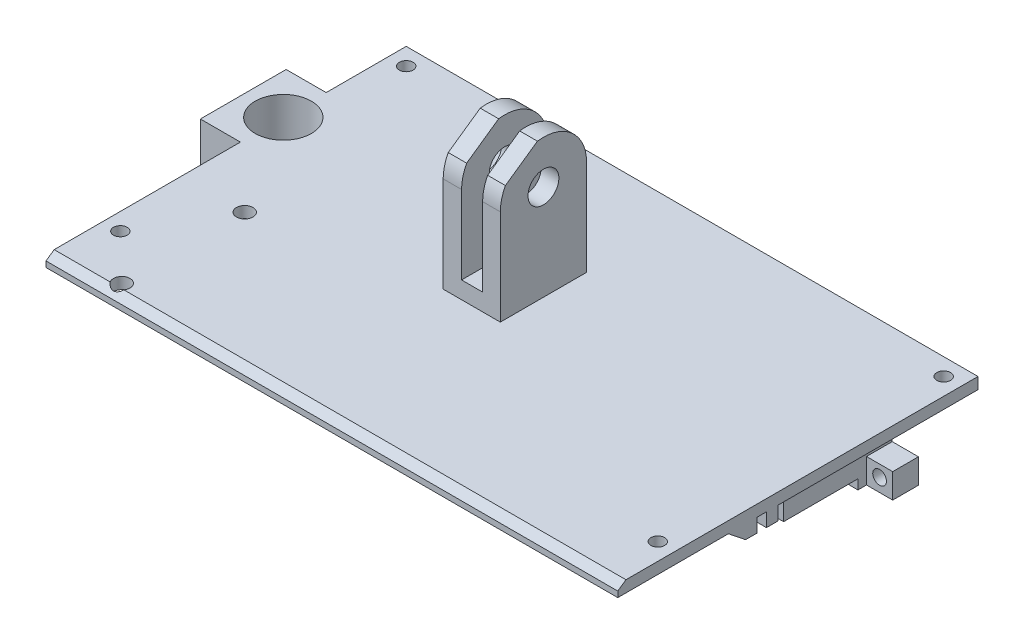
SolidWorks part; units mm, degrees
other "标注1"
sketch "草图30" plane through (-53.9, -44.7, 30) normal (-0.0815, -0.3453, 0.9349) x (0.9738, -0.2273, 0.0009)
other "标注2"
sketch "草图31" plane through (-53.9, -44.7, 30) normal (-0.0815, -0.3453, 0.9349) x (0.9738, -0.2273, 0.0009)
other "标注3"
sketch "草图32" plane through (-53.9, -44.7, 30) normal (-0.0964, -0.7087, 0.6989) x (0.9696, 0.0917, 0.2268)
ref_plane "前视基准面" through (0, 0, 0) normal (0, 0, 1) x (1, 0, 0)
ref_plane "上视基准面" through (0, 0, 0) normal (0, 1, 0) x (1, 0, 0)
ref_plane "右视基准面" through (0, 0, 0) normal (1, 0, 0) x (0, 0, -1)
other "Configuration Table"
sketch "草图1" plane through (0, 0, 0) normal (1, 0, 0) x (0, 0, -1)
  line L0 (0, -2.7) -> (0, -13.7)
  line L1 (-7.54, 0) -> (7.54, 0)
  line L2 (-7.54, 0) -> (-7.54, -13.7)
  line L3 (-7.54, -13.7) -> (7.54, -13.7)
  line L4 (7.54, 0) -> (7.54, -13.7)
  circle A0 centre (0, 0) radius 2.7
  circle A1 centre (0, 0) radius 7.54
  dimension "D1" = 5.4
  dimension "D3" = 11
  dimension "D2" = 4.84
extrude "凸台-拉伸1" add sketch "草图1" along normal blind 3.1 contours L0 A1 L1 A0 | L1 A1 L0 A0 | A1 L2 L3 L0 | L1 A1 A0 | A1 L0 L3 L4
sketch "草图2" plane through (0, -13.7, 0) normal (0, -1, 0) x (1, 0, 0)
  line L1 (3.1, 7.54) -> (-6.9, 7.54)
  line L2 (3.1, 7.54) -> (3.1, -7.54)
  line L3 (3.1, -7.54) -> (-6.9, -7.54)
  line L4 (0, 7.54) -> (0, -7.54)
  line L5 (0, -7.54) -> (3.1, -7.54)
  line L6 (3.1, -7.54) -> (3.1, 7.54)
  line L7 (3.1, 7.54) -> (0, 7.54)
  line L8 (0, 7.54) -> (0, -7.54)
  line L9 (0, -7.54) -> (3.1, -7.54)
  line L10 (3.1, -7.54) -> (3.1, 7.54)
  line L11 (3.1, 7.54) -> (0, 7.54)
  line L12 (-6.9, 7.54) -> (-6.9, -7.54)
  line L13 (-6.9, 7.54) -> (-3.68, 7.54)
  line L14 (-6.9, 7.54) -> (-6.9, -7.54)
  line L15 (-6.9, -7.54) -> (-3.68, -7.54)
  line L16 (-3.68, 7.54) -> (-3.68, -7.54)
  line M9 (0, 7.54) -> (0, -7.54)
  line M10 (0, -7.54) -> (3.1, -7.54)
  line M11 (3.1, -7.54) -> (3.1, 7.54)
  line M12 (3.1, 7.54) -> (0, 7.54)
  dimension "D2" = 10
  dimension "D3" = 3.22
  dimension "D1" = 0
extrude "凸台-拉伸2" add sketch "草图2" along normal blind 3 contours M12 M9 M10 M11 | L1 L16 L3 M9 | L16 L1 L12 L3
sketch "草图3" plane through (0, -13.7, 0) normal (0, 1, 0) x (1, 0, 0)
  line L1 (-6.9, 7.54) -> (-3.68, 7.54)
  line L2 (-6.9, 7.54) -> (-6.9, -7.54)
  line L3 (-6.9, -7.54) -> (-3.68, -7.54)
  line L4 (-6.9, -7.54) -> (0, -7.54)
  line L5 (0, -7.54) -> (0, 7.54)
  line L6 (0, 7.54) -> (-6.9, 7.54)
  line L7 (-6.9, 7.54) -> (-6.9, -7.54)
  line L8 (-6.9, -7.54) -> (0, -7.54)
  line L9 (0, -7.54) -> (0, 7.54)
  line L10 (0, 7.54) -> (-6.9, 7.54)
  line L11 (-6.9, 7.54) -> (-6.9, -7.54)
  line L12 (-3.68, 7.54) -> (-3.68, -7.54)
  line M5 (-6.9, -7.54) -> (0, -7.54)
  line M7 (0, 7.54) -> (-6.9, 7.54)
  line M8 (-6.9, 7.54) -> (-6.9, -7.54)
  dimension "D2" = 3.22
  dimension "D1" = 0
extrude "凸台-拉伸3" add sketch "草图3" along normal blind 24 contours L12 M7 M8 M5
sketch "草图4" plane through (-6.9, 0, 0) normal (-1, 0, 0) x (0, 0, 1)
  line L3 (7.54, -16.7) -> (7.54, 0)
  line L4 (-7.54, -16.7) -> (7.54, -16.7)
  line L5 (-7.54, 0) -> (-7.54, -16.7)
  line L6 (7.54, -16.7) -> (7.54, 0)
  line L7 (-7.54, -16.7) -> (7.54, -16.7)
  line L8 (-7.54, 0) -> (-7.54, -16.7)
  line L10 (7.54, -16.7) -> (7.54, 10.3)
  line L11 (7.54, 10.3) -> (-7.54, 10.3)
  line L12 (-7.54, 10.3) -> (-7.54, -16.7)
  line L13 (-7.54, -16.7) -> (7.54, -16.7)
  line L14 (7.54, -16.7) -> (7.54, 10.3)
  line L15 (7.54, 10.3) -> (-7.54, 10.3)
  line L16 (-7.54, 10.3) -> (-7.54, -16.7)
  line L17 (-7.54, -16.7) -> (7.54, -16.7)
  circle A0 centre (0, 0) radius 2.7 construction
  arc A1 (7.54, 0) -> (-7.54, 0) centre (0, 0) ccw
  arc A2 (7.54, 0) -> (-7.54, 0) centre (0, 0) ccw
  circle A3 centre (0, 0) radius 2.7
  line M9 (7.54, -16.7) -> (7.54, 10.3)
  line M10 (7.54, 10.3) -> (-7.54, 10.3)
  line M11 (-7.54, 10.3) -> (-7.54, -16.7)
  dimension "D1" = 0
  dimension "D2" = 0
extrude "切除-拉伸1" cut sketch "草图4" against normal blind 24 contours A2 M9 M10 M11 | A3
sketch "草图5" plane through (0, -16.7, 0) normal (0, -1, 0) x (1, 0, 0)
  line L0 (-6.9, 7.54) -> (3.1, -7.54)
  line L2 (-46.9, -20) -> (43.1, -20)
  line L3 (-46.9, -20) -> (-46.9, 20)
  line L4 (3.1, 7.54) -> (-6.9, 7.54)
  line L5 (-6.9, 7.54) -> (-6.9, -7.54)
  line L6 (-6.9, -7.54) -> (3.1, -7.54)
  line L7 (3.1, -7.54) -> (3.1, 7.54)
  line L8 (3.1, 7.54) -> (-6.9, 7.54)
  line L9 (-6.9, 7.54) -> (-6.9, -7.54)
  line L10 (-6.9, -7.54) -> (3.1, -7.54)
  line L11 (3.1, -7.54) -> (3.1, 7.54)
  line L12 (-46.9, 20) -> (43.1, 20)
  line L13 (43.1, -20) -> (43.1, 20)
  line L14 (-46.9, -20) -> (43.1, 20) construction
  line L15 (-46.9, 20) -> (43.1, -20) construction
  point P2 (-1.9, 0)
  line M7 (3.1, 7.54) -> (-6.9, 7.54)
  line M8 (-6.9, 7.54) -> (-6.9, -7.54)
  line M9 (-6.9, -7.54) -> (3.1, -7.54)
  line M10 (3.1, -7.54) -> (3.1, 7.54)
  dimension "D2" = 90
  dimension "D3" = 40
  dimension "D1" = 0
extrude "凸台-拉伸4" add sketch "草图5" along normal blind 2 contours L2 L13 L12 L3 M7 M10 M9 M8 | L0 M8 M9 | L0 M7 M10
sketch "草图6" plane through (0, -18.7, 0) normal (0, -1, 0) x (1, 0, 0)
  line L0 (-39.9, -20) -> (36.1, -20)
  line L1 (-41.9, -20) -> (-41.9, 3)
  line L2 (-39.9, -20) -> (36.1, -20)
  line L3 (-39.9, -20) -> (-39.9, 1)
  line L4 (-46.9, -20) -> (43.1, -20)
  line L5 (43.1, -20) -> (43.1, 20)
  line L6 (43.1, 20) -> (-46.9, 20)
  line L7 (-46.9, 20) -> (-46.9, -20)
  line L8 (-46.9, -20) -> (43.1, -20)
  line L9 (43.1, -20) -> (43.1, 20)
  line L10 (43.1, 20) -> (-46.9, 20)
  line L11 (-46.9, 20) -> (-46.9, -20)
  line L12 (-39.9, 1) -> (36.1, 1)
  line L13 (36.1, -20) -> (36.1, 1)
  line L14 (-41.9, 3) -> (38.1, 3)
  line L15 (38.1, -20) -> (38.1, 3)
  line L17 (-41.9, -20) -> (38.1, -20)
  line L18 (-41.9, -20) -> (-41.9, -22)
  line L19 (-41.9, -22) -> (38.1, -22)
  line L20 (38.1, -20) -> (38.1, -22)
  point P7 (-1.9, -20)
  line M11 (-46.9, -20) -> (43.1, -20)
  dimension "D2" = 76
  dimension "D3" = 21
  dimension "D5" = 2
  dimension "D1" = 0
  dimension "D4" = 2
extrude "凸台-拉伸6" add sketch "草图6" along normal blind 18 and the other way up to surface contours L15 L14 L1 L3 L12 L13 M11 | L20 L18 L19 M11
sketch "草图7" plane through (0, -36.7, 0) normal (0, -1, 0) x (1, 0, 0)
  line L1 (38.1, 3) -> (28.1, 3)
  line L2 (38.1, 3) -> (38.1, -7)
  line L3 (38.1, -7) -> (28.1, -7)
  line L4 (-41.9, -22) -> (38.1, -22)
  line L5 (38.1, -22) -> (38.1, 3)
  line L6 (38.1, 3) -> (-41.9, 3)
  line L7 (-41.9, 3) -> (-41.9, -22)
  line L8 (-41.9, -22) -> (38.1, -22)
  line L9 (38.1, -22) -> (38.1, 3)
  line L10 (38.1, 3) -> (-41.9, 3)
  line L11 (-41.9, 3) -> (-41.9, -22)
  line L12 (28.1, 3) -> (28.1, -7)
  line L13 (-41.9, -22) -> (-31.9, -22)
  line L14 (-41.9, -22) -> (-41.9, -12)
  line L15 (-41.9, -12) -> (-31.9, -12)
  line L16 (-31.9, -22) -> (-31.9, -12)
  line M9 (-41.9, -22) -> (38.1, -22)
  line M10 (38.1, -22) -> (38.1, 3)
  line M11 (38.1, 3) -> (-41.9, 3)
  line M13 (36.1, 1) -> (36.1, -20)
  line M14 (36.1, -20) -> (-39.9, -20)
  line M15 (-39.9, -20) -> (-39.9, 1)
  line M16 (-39.9, 1) -> (36.1, 1)
  dimension "D2" = 10
  dimension "D3" = 10
  dimension "D4" = 10
  dimension "D5" = 10
  dimension "D1" = 0
extrude "切除-拉伸2" cut sketch "草图7" against normal up to surface (18 mm away) contours L12 L3 M11 M16 M13 M10 | L16 L15 L11 M9 M14 M15 up to face at (-1.9, -18.7, -4.25)
sketch "草图8" plane through (0, -18.7, 0) normal (0, -1, 0) x (1, 0, 0)
  line L0 (-41.9, 3) -> (-41.9, 11)
  line L1 (-43.9, 9) -> (-43.9, 14.65)
  line L2 (-41.9, 11) -> (8.1, 11)
  line L3 (-41.9, 11) -> (-41.9, 12.65)
  line L4 (-41.9, 12.65) -> (8.1, 12.65)
  line L5 (8.1, 11) -> (8.1, 12.65)
  line L6 (-43.9, 14.65) -> (10.1, 14.65)
  line L7 (10.1, 9) -> (10.1, 14.65)
  line L8 (-43.9, 9) -> (10.1, 9)
  line L9 (-41.9, 12.65) -> (-43.9, 12.65)
  line L10 (-41.9, 11) -> (-43.9, 11)
  line L11 (8.1, 12.65) -> (10.1, 12.65)
  line L12 (36.1, -7) -> (38.1, -7)
  line L13 (38.1, -7) -> (38.1, -20)
  line L14 (38.1, -20) -> (43.1, -20)
  line L15 (43.1, -20) -> (43.1, 20)
  line L16 (43.1, 20) -> (-46.9, 20)
  line L17 (-46.9, 20) -> (-46.9, -20)
  line L18 (-46.9, -20) -> (-41.9, -20)
  line L19 (-41.9, -20) -> (-41.9, -22)
  line L20 (-41.9, -22) -> (-31.9, -22)
  line L21 (-31.9, -22) -> (-31.9, -20)
  line L22 (-31.9, -20) -> (36.1, -20)
  line L23 (36.1, -20) -> (36.1, -7)
  line L24 (36.1, -7) -> (38.1, -7)
  line L25 (38.1, -7) -> (38.1, -20)
  line L26 (38.1, -20) -> (43.1, -20)
  line L27 (43.1, -20) -> (43.1, 20)
  line L28 (43.1, 20) -> (-46.9, 20)
  line L29 (-46.9, 20) -> (-46.9, -20)
  line L30 (-46.9, -20) -> (-41.9, -20)
  line L31 (-41.9, -20) -> (-41.9, -22)
  line L32 (-41.9, -22) -> (-31.9, -22)
  line L33 (-31.9, -22) -> (-31.9, -20)
  line L34 (-31.9, -20) -> (36.1, -20)
  line L35 (36.1, -20) -> (36.1, -7)
  line L36 (8.1, 11) -> (10.1, 11)
  dimension "D2" = 8
  dimension "D3" = 50
  dimension "D4" = 1.65
  dimension "D1" = 0
  dimension "D5" = 2
extrude "凸台-拉伸8" add sketch "草图8" along normal blind 2.4 contours L4 L11 L7 L6 L1 L9 | L36 L2 L0 L8 L7 | L0 L10 L1 L8
sketch "草图9" plane through (0, -21.1, 0) normal (0, -1, 0) x (1, 0, 0)
  line L0 (43.1, -20) -> (43.1, 20) construction
  line L1 (10.1, 14.65) -> (43.1, 14.65)
  line L2 (10.1, 14.65) -> (10.1, 12.65)
  line L3 (10.1, 12.65) -> (43.1, 12.65)
  line L4 (-43.9, 12.65) -> (10.1, 12.65)
  line L5 (10.1, 12.65) -> (10.1, 14.65)
  line L6 (10.1, 14.65) -> (-43.9, 14.65)
  line L7 (-43.9, 14.65) -> (-43.9, 12.65)
  line L8 (-43.9, 12.65) -> (10.1, 12.65)
  line L9 (10.1, 12.65) -> (10.1, 14.65)
  line L10 (10.1, 14.65) -> (-43.9, 14.65)
  line L11 (-43.9, 14.65) -> (-43.9, 12.65)
  line L12 (10.1, 11) -> (-43.9, 11)
  line L13 (-43.9, 11) -> (-43.9, 9)
  line L14 (-43.9, 9) -> (10.1, 9)
  line L15 (10.1, 9) -> (10.1, 11)
  line L16 (10.1, 11) -> (-43.9, 11)
  line L17 (-43.9, 11) -> (-43.9, 9)
  line L18 (-43.9, 9) -> (10.1, 9)
  line L19 (10.1, 9) -> (10.1, 11)
  line L20 (43.1, 14.65) -> (43.1, 12.65)
  line L21 (-46.9, -20) -> (-46.9, 20) construction
  line L22 (10.1, 11) -> (43.1, 11)
  line L23 (10.1, 11) -> (10.1, 9)
  line L24 (10.1, 9) -> (43.1, 9)
  line L25 (43.1, 11) -> (43.1, 9)
  line L26 (-43.9, 11) -> (-46.9, 11)
  line L27 (-43.9, 11) -> (-43.9, 9)
  line L28 (-43.9, 9) -> (-46.9, 9)
  line L29 (-46.9, 11) -> (-46.9, 9)
  line L31 (-43.9, 14.65) -> (-46.9, 14.65)
  line L32 (-43.9, 14.65) -> (-43.9, 12.65)
  line L33 (-43.9, 12.65) -> (-46.9, 12.65)
  line L34 (-46.9, 14.65) -> (-46.9, 12.65)
  line M10 (10.1, 12.65) -> (10.1, 14.65)
  line M12 (-43.9, 14.65) -> (-43.9, 12.65)
  dimension "D1" = 0
  dimension "D2" = 0
extrude "凸台-拉伸9" add sketch "草图9" against normal up to surface (2.4 mm away) contours L20 L1 L3 M10 | L25 L22 L19 L24 | L31 L34 L33 M12 | L26 L29 L28 L17 up to face at (-16.9, -18.7, 10)
sketch "草图10" plane through (0, -21.1, 0) normal (0, -1, 0) x (1, 0, 0)
  line L1 (-46.9, 14.65) -> (-36.9, 14.65)
  line L2 (-46.9, 14.65) -> (-46.9, 12.65)
  line L3 (-46.9, 12.65) -> (-36.9, 12.65)
  line L4 (-46.9, 12.65) -> (43.1, 12.65)
  line L5 (43.1, 12.65) -> (43.1, 14.65)
  line L6 (43.1, 14.65) -> (-46.9, 14.65)
  line L7 (-46.9, 14.65) -> (-46.9, 12.65)
  line L8 (-46.9, 12.65) -> (43.1, 12.65)
  line L9 (43.1, 12.65) -> (43.1, 14.65)
  line L10 (43.1, 14.65) -> (-46.9, 14.65)
  line L11 (-46.9, 14.65) -> (-46.9, 12.65)
  line L12 (43.1, 11) -> (-46.9, 11)
  line L13 (-46.9, 11) -> (-46.9, 9)
  line L14 (-46.9, 9) -> (43.1, 9)
  line L15 (43.1, 9) -> (43.1, 11)
  line L16 (43.1, 11) -> (-46.9, 11)
  line L17 (-46.9, 11) -> (-46.9, 9)
  line L18 (-46.9, 9) -> (43.1, 9)
  line L19 (43.1, 9) -> (43.1, 11)
  line L20 (-36.9, 14.65) -> (-36.9, 12.65)
  line L21 (-36.9, 14.65) -> (-26.9, 14.65)
  line L22 (-36.9, 14.65) -> (-36.9, 12.65)
  line L23 (-36.9, 12.65) -> (-26.9, 12.65)
  line L24 (-26.9, 14.65) -> (-26.9, 12.65)
  line L25 (-36.9, 11) -> (-26.9, 11)
  line L26 (-36.9, 11) -> (-36.9, 9)
  line L27 (-36.9, 9) -> (-26.9, 9)
  line L28 (-26.9, 11) -> (-26.9, 9)
  line L29 (-36.9, 12.65) -> (-34.9, 12.65)
  line L30 (-36.9, 12.65) -> (-36.9, 11)
  line L31 (-36.9, 11) -> (-34.9, 11)
  line L32 (-34.9, 12.65) -> (-34.9, 11)
  line M9 (-46.9, 12.65) -> (43.1, 12.65)
  line M11 (43.1, 14.65) -> (-46.9, 14.65)
  line M12 (-46.9, 14.65) -> (-46.9, 12.65)
  dimension "D3" = 10
  dimension "D4" = 10
  dimension "D5" = 10
  dimension "D6" = 2
  dimension "D1" = 0
  dimension "D2" = 0
extrude "凸台-拉伸10" add sketch "草图10" along normal up to surface (15.6 mm away) contours L24 L10 L20 L23 M9 | L32 L30 L25 M9 | L28 L16 L25 L26 L18 | L20 M11 M12 M9 | L26 L16 L17 L18 up to face at (-17.9, -36.7, -2.6667)
sketch "草图11" plane through (0, -36.7, 0) normal (0, -1, 0) x (1, 0, 0)
  line L1 (-41.9, -12) -> (-53.9, -12)
  line L2 (-41.9, -12) -> (-41.9, 3)
  line L3 (-41.9, 3) -> (-53.9, 3)
  line L4 (-53.9, -12) -> (-53.9, 3)
  line L6 (28.1, 1) -> (28.1, 3)
  line L7 (28.1, 3) -> (-41.9, 3)
  line L8 (-41.9, 3) -> (-41.9, -12)
  line L9 (-41.9, -12) -> (-39.9, -12)
  line L10 (-39.9, -12) -> (-39.9, 1)
  line L11 (-39.9, 1) -> (28.1, 1)
  line L12 (28.1, 1) -> (28.1, 3)
  line L13 (28.1, 3) -> (-41.9, 3)
  line L14 (-41.9, 3) -> (-41.9, -12)
  line L15 (-41.9, -12) -> (-39.9, -12)
  line L16 (-39.9, -12) -> (-39.9, 1)
  line L17 (-39.9, 1) -> (28.1, 1)
  line M10 (-41.9, 3) -> (-41.9, -12)
  dimension "D2" = 12
  dimension "D1" = 0
extrude "凸台-拉伸11" add sketch "草图11" against normal up to surface (20 mm away) contours L4 L1 L3 M10 up to face at (-1.9, -16.7, 0)
sketch "草图12" plane through (0, -36.7, 0) normal (0, -1, 0) x (1, 0, 0)
  line L0 (-39.9, -12) -> (-53.9, 3)
  line L6 (28.1, 1) -> (28.1, 3)
  line L7 (28.1, 3) -> (-53.9, 3)
  line L8 (-53.9, 3) -> (-53.9, -12)
  line L9 (-53.9, -12) -> (-39.9, -12)
  line L10 (-39.9, -12) -> (-39.9, 1)
  line L11 (-39.9, 1) -> (28.1, 1)
  line L12 (28.1, 1) -> (28.1, 3)
  line L13 (28.1, 3) -> (-53.9, 3)
  line L14 (-53.9, 3) -> (-53.9, -12)
  line L15 (-53.9, -12) -> (-39.9, -12)
  line L16 (-39.9, -12) -> (-39.9, 1)
  line L17 (-39.9, 1) -> (28.1, 1)
  circle A0 centre (-46.9, -4.5) radius 4.115
  dimension "D2" = 8.23
  dimension "D1" = 0
extrude "切除-拉伸3" cut sketch "草图12" against normal up to surface (20 mm away) contours L0 A0 | L0 A0 up to face at (-18.0667, -16.7, -8.5)
sketch "草图13" plane through (0, -18.7, 0) normal (0, -1, 0) x (1, 0, 0)
  line L1 (-46.9, -20) -> (43.1, -20)
  line L2 (-46.9, -20) -> (-46.9, -26)
  line L3 (-46.9, -26) -> (43.1, -26)
  line L4 (43.1, -20) -> (43.1, -26)
  line L6 (38.1, -22) -> (38.1, -7)
  line L7 (38.1, -7) -> (36.1, -7)
  line L8 (36.1, -7) -> (36.1, -20)
  line L9 (36.1, -20) -> (-31.9, -20)
  line L10 (-31.9, -20) -> (-31.9, -22)
  line L11 (-31.9, -22) -> (38.1, -22)
  line L12 (38.1, -22) -> (38.1, -7)
  line L13 (38.1, -7) -> (36.1, -7)
  line L14 (36.1, -7) -> (36.1, -20)
  line L15 (36.1, -20) -> (-31.9, -20)
  line L16 (-31.9, -20) -> (-31.9, -22)
  line L17 (-31.9, -22) -> (38.1, -22)
  line L18 (-39.9, -12) -> (-46.9, -12)
  line L19 (-46.9, -12) -> (-46.9, -20)
  line L20 (-46.9, -20) -> (-41.9, -20)
  line L21 (-41.9, -20) -> (-41.9, -22)
  line L22 (-41.9, -22) -> (-31.9, -22)
  line L23 (-31.9, -22) -> (-31.9, -20)
  line L24 (-31.9, -20) -> (36.1, -20)
  line L25 (36.1, -20) -> (36.1, -7)
  line L26 (36.1, -7) -> (38.1, -7)
  line L27 (38.1, -7) -> (38.1, -20)
  line L28 (38.1, -20) -> (43.1, -20)
  line L29 (43.1, -20) -> (43.1, 9)
  line L30 (43.1, 9) -> (-46.9, 9)
  line L31 (-46.9, 9) -> (-46.9, 3)
  line L32 (-46.9, 3) -> (28.1, 3)
  line L33 (28.1, 3) -> (28.1, 1)
  line L34 (28.1, 1) -> (-39.9, 1)
  line L35 (-39.9, 1) -> (-39.9, -12)
  line L36 (-39.9, -12) -> (-46.9, -12)
  line L37 (-46.9, -12) -> (-46.9, -20)
  line L38 (-46.9, -20) -> (-41.9, -20)
  line L39 (-41.9, -20) -> (-41.9, -22)
  line L40 (-41.9, -22) -> (-31.9, -22)
  line L41 (-31.9, -22) -> (-31.9, -20)
  line L42 (-31.9, -20) -> (36.1, -20)
  line L43 (36.1, -20) -> (36.1, -7)
  line L44 (36.1, -7) -> (38.1, -7)
  line L45 (38.1, -7) -> (38.1, -20)
  line L46 (38.1, -20) -> (43.1, -20)
  line L47 (43.1, -20) -> (43.1, 9)
  line L48 (43.1, 9) -> (-46.9, 9)
  line L49 (-46.9, 9) -> (-46.9, 3)
  line L50 (-46.9, 3) -> (28.1, 3)
  line L51 (28.1, 3) -> (28.1, 1)
  line L52 (28.1, 1) -> (-39.9, 1)
  line L53 (-39.9, 1) -> (-39.9, -12)
  line M28 (-46.9, -20) -> (-41.9, -20)
  line M29 (-41.9, -20) -> (-41.9, -22)
  line M30 (-41.9, -22) -> (-31.9, -22)
  line M36 (38.1, -20) -> (43.1, -20)
  dimension "D3" = 6
  dimension "D1" = 0
  dimension "D2" = 0
extrude "凸台-拉伸12" add sketch "草图13" against normal up to surface (2 mm away) contours L17 L2 L3 L4 L12 M30 M29 M28 M36 up to face at (-46.9, -16.7, -8.615)
sketch "草图14" plane through (0, 0, 14.65) normal (0, 0, 1) x (1, 0, 0)
  line L1 (-36.9, -36.7) -> (-46.9, -36.7)
  line L2 (-36.9, -36.7) -> (-36.9, -18.7)
  line L3 (-36.9, -18.7) -> (-46.9, -18.7)
  line L4 (-46.9, -36.7) -> (-46.9, -18.7)
  line L6 (43.1, -18.7) -> (-46.9, -18.7)
  line L7 (-46.9, -18.7) -> (-46.9, -36.7)
  line L8 (-46.9, -36.7) -> (-26.9, -36.7)
  line L9 (-26.9, -36.7) -> (-26.9, -21.1)
  line L10 (-26.9, -21.1) -> (43.1, -21.1)
  line L11 (43.1, -21.1) -> (43.1, -18.7)
  line L12 (43.1, -18.7) -> (-46.9, -18.7)
  line L13 (-46.9, -18.7) -> (-46.9, -36.7)
  line L14 (-46.9, -36.7) -> (-26.9, -36.7)
  line L15 (-26.9, -36.7) -> (-26.9, -21.1)
  line L16 (-26.9, -21.1) -> (43.1, -21.1)
  line L17 (43.1, -21.1) -> (43.1, -18.7)
  line L22 (43.1, -18.7) -> (-46.9, -18.7)
  line L23 (-46.9, -18.7) -> (-46.9, -36.7)
  line L24 (-46.9, -36.7) -> (-36.9, -36.7)
  line L25 (-36.9, -36.7) -> (-36.9, -21.1)
  line L26 (-36.9, -21.1) -> (-34.9, -21.1)
  line L27 (-34.9, -21.1) -> (-34.9, -36.7)
  line L28 (-34.9, -36.7) -> (-26.9, -36.7)
  line L29 (-26.9, -36.7) -> (-26.9, -21.1)
  line L30 (-26.9, -21.1) -> (43.1, -21.1)
  line L31 (43.1, -21.1) -> (43.1, -18.7)
  line L32 (43.1, -18.7) -> (-46.9, -18.7)
  line L33 (-46.9, -18.7) -> (-46.9, -36.7)
  line L34 (-46.9, -36.7) -> (-36.9, -36.7)
  line L35 (-36.9, -36.7) -> (-36.9, -21.1)
  line L36 (-36.9, -21.1) -> (-34.9, -21.1)
  line L37 (-34.9, -21.1) -> (-34.9, -36.7)
  line L38 (-34.9, -36.7) -> (-26.9, -36.7)
  line L39 (-26.9, -36.7) -> (-26.9, -21.1)
  line L40 (-26.9, -21.1) -> (43.1, -21.1)
  line L41 (43.1, -21.1) -> (43.1, -18.7)
  line M17 (43.1, -18.7) -> (-46.9, -18.7)
  line M18 (-46.9, -18.7) -> (-46.9, -36.7)
  line M19 (-46.9, -36.7) -> (-26.9, -36.7)
  dimension "D1" = 0
  dimension "D2" = 0
extrude "切除-拉伸4" cut sketch "草图14" against normal up to surface (3.65 mm away) contours L2 M19 M17 M18 up to face at (-20.5, -26.86, 11)
sketch "草图15" plane through (0, 0, 14.65) normal (0, 0, 1) x (1, 0, 0)
  line L0 (-26.9, -21.1) -> (-36.9, -21.1)
  line L6 (-36.9, -18.7) -> (-36.9, -36.7)
  line L7 (-36.9, -36.7) -> (-26.9, -36.7)
  line L8 (-26.9, -36.7) -> (-26.9, -21.1)
  line L9 (-26.9, -21.1) -> (43.1, -21.1)
  line L10 (43.1, -21.1) -> (43.1, -18.7)
  line L11 (43.1, -18.7) -> (-36.9, -18.7)
  line L12 (-36.9, -18.7) -> (-36.9, -36.7)
  line L13 (-36.9, -36.7) -> (-26.9, -36.7)
  line L14 (-26.9, -36.7) -> (-26.9, -21.1)
  line L15 (-26.9, -21.1) -> (43.1, -21.1)
  line L16 (43.1, -21.1) -> (43.1, -18.7)
  line L17 (43.1, -18.7) -> (-36.9, -18.7)
  line M7 (-36.9, -18.7) -> (-36.9, -36.7)
  line M8 (-36.9, -36.7) -> (-26.9, -36.7)
  line M9 (-26.9, -36.7) -> (-26.9, -21.1)
  dimension "D1" = 0
extrude "切除-拉伸5" cut sketch "草图15" against normal up to surface (3.65 mm away) contours L0 M9 M7 M8 up to face at (-20.5, -26.86, 11)
sketch "草图17" plane through (0, 0, 11) normal (0, 0, 1) x (1, 0, 0)
  line L1 (-46.9, -18.7) -> (-26.9, -18.7)
  line L2 (-46.9, -18.7) -> (-46.9, -44.7)
  line L3 (-46.9, -44.7) -> (-26.9, -44.7)
  line L4 (-26.9, -18.7) -> (-26.9, -44.7)
  line L6 (-26.9, -36.7) -> (-26.9, -21.1)
  line L7 (-26.9, -21.1) -> (43.1, -21.1)
  line L8 (43.1, -21.1) -> (43.1, -18.7)
  line L9 (43.1, -18.7) -> (-46.9, -18.7)
  line L10 (-46.9, -18.7) -> (-46.9, -36.7)
  line L11 (-46.9, -36.7) -> (-26.9, -36.7)
  line L12 (-26.9, -36.7) -> (-26.9, -21.1)
  line L13 (-26.9, -21.1) -> (43.1, -21.1)
  line L14 (43.1, -21.1) -> (43.1, -18.7)
  line L15 (43.1, -18.7) -> (-46.9, -18.7)
  line L16 (-46.9, -18.7) -> (-46.9, -36.7)
  line L17 (-46.9, -36.7) -> (-26.9, -36.7)
  line M13 (-46.9, -36.7) -> (-26.9, -36.7)
  dimension "D2" = 26
  dimension "D1" = 0
extrude "凸台-拉伸13" add sketch "草图17" against normal up to surface (2 mm away) contours L4 L2 L3 M13 up to face at (-10.2333, -25.5, 9)
sketch "草图18" plane through (0, 0, 11) normal (0, 0, 1) x (1, 0, 0)
  line L0 (-35.9, -44.7) -> (-35.9, -43.9)
  line L1 (-46.9, -18.7) -> (-35.9, -18.7)
  line L2 (-46.9, -18.7) -> (-46.9, -44.7)
  line L3 (-46.9, -44.7) -> (-35.9, -44.7)
  line L4 (-35.9, -18.7) -> (-35.9, -44.7)
  line L5 (-35.9, -18.7) -> (-35.9, -19.5)
  line L6 (-26.9, -44.7) -> (-26.9, -21.1)
  line L7 (-26.9, -21.1) -> (43.1, -21.1)
  line L8 (43.1, -21.1) -> (43.1, -18.7)
  line L9 (43.1, -18.7) -> (-46.9, -18.7)
  line L10 (-46.9, -18.7) -> (-46.9, -44.7)
  line L11 (-46.9, -44.7) -> (-26.9, -44.7)
  line L12 (-26.9, -44.7) -> (-26.9, -21.1)
  line L13 (-26.9, -21.1) -> (43.1, -21.1)
  line L14 (43.1, -21.1) -> (43.1, -18.7)
  line L15 (43.1, -18.7) -> (-46.9, -18.7)
  line L16 (-46.9, -18.7) -> (-46.9, -44.7)
  line L17 (-46.9, -44.7) -> (-26.9, -44.7)
  circle A0 centre (-35.9, -42.45) radius 1.45
  circle A1 centre (-35.9, -20.95) radius 1.45
  dimension "D4" = 2.9
  dimension "D6" = 2.9
  dimension "D2" = 11
  dimension "D3" = 0.8
  dimension "D5" = 0.8
  dimension "D1" = 0
extrude "切除-拉伸6" cut sketch "草图18" against normal up to surface (2 mm away) contours L4 A1 | L4 A1 | L4 A0 | L4 A0 up to face at (-10.2333, -28.1667, 9)
sketch "草图19" plane through (0, 0, 14.65) normal (0, 0, 1) x (1, 0, 0)
  line L0 (-26.9, -44.7) -> (-26.9, -21.1) construction
  line L1 (-26.9, -44.7) -> (-26.9, -21.1)
  line L3 (-36.9, -21.1) -> (-26.9, -21.1)
  line L4 (-36.9, -18.7) -> (-36.9, -21.1)
  line L5 (-36.9, -21.1) -> (43.1, -21.1)
  line L6 (43.1, -21.1) -> (43.1, -18.7)
  line L7 (43.1, -18.7) -> (-36.9, -18.7)
  line L8 (-36.9, -18.7) -> (-36.9, -21.1)
  line L9 (-36.9, -21.1) -> (43.1, -21.1)
  line L10 (43.1, -21.1) -> (43.1, -18.7)
  line L11 (43.1, -18.7) -> (-36.9, -18.7)
  line L12 (-36.9, -21.1) -> (-36.9, -18.7)
  line L13 (-36.9, -18.7) -> (-26.9, -18.7)
  line L14 (-26.9, -21.1) -> (-26.9, -18.7)
  line M5 (-36.9, -18.7) -> (-36.9, -21.1)
  line M6 (-36.9, -21.1) -> (43.1, -21.1)
  dimension "D1" = 0
extrude "切除-拉伸7" cut sketch "草图19" against normal up to surface (3.65 mm away) contours L14 L11 M6 M5 up to face at (-34.45, -20.95, 11)
sketch "草图20" plane through (0, -36.7, 0) normal (0, -1, 0) x (1, 0, 0)
  circle A0 centre (-46.9, -4.5) radius 4.71
  dimension "D1" = 9.42
extrude "切除-拉伸8" cut sketch "草图20" against normal up to surface (20 mm away) contours A0 up to face at (-26.15, -16.7, -3.75)
sketch "草图21" plane through (0, 0, 20) normal (0, 0, 1) x (1, 0, 0)
  line L4 (43.1, -16.7) -> (-46.9, -16.7)
  line L5 (-46.9, -16.7) -> (-46.9, -18.7)
  line L6 (-46.9, -18.7) -> (43.1, -18.7)
  line L7 (43.1, -18.7) -> (43.1, -16.7)
  line L8 (43.1, -16.7) -> (-46.9, -16.7)
  line L9 (-46.9, -16.7) -> (-46.9, -18.7)
  line L10 (-46.9, -18.7) -> (43.1, -18.7)
  line L11 (43.1, -18.7) -> (43.1, -16.7)
  dimension "D1" = 0
extrude "凸台-拉伸14" add sketch "草图21" along normal blind 10
sketch "草图22" plane through (43.1, 0, 0) normal (1, 0, 0) x (0, 0, -1)
  line L12 (26, -16.7) -> (-30, -16.7)
  line L13 (-30, -16.7) -> (-30, -18.7)
  line L14 (-30, -18.7) -> (-14.65, -18.7)
  line L15 (-14.65, -18.7) -> (-14.65, -21.1)
  line L16 (-14.65, -21.1) -> (-12.65, -21.1)
  line L17 (-12.65, -21.1) -> (-12.65, -18.7)
  line L18 (-12.65, -18.7) -> (-11, -18.7)
  line L19 (-11, -18.7) -> (-11, -21.1)
  line L20 (-11, -21.1) -> (-9, -21.1)
  line L21 (-9, -21.1) -> (-9, -18.7)
  line L22 (-9, -18.7) -> (26, -18.7)
  line L23 (26, -18.7) -> (26, -16.7)
  line L24 (26, -16.7) -> (-30, -16.7)
  line L25 (-30, -16.7) -> (-30, -18.7)
  line L26 (-30, -18.7) -> (-14.65, -18.7)
  line L27 (-14.65, -18.7) -> (-14.65, -21.1)
  line L28 (-14.65, -21.1) -> (-12.65, -21.1)
  line L29 (-12.65, -21.1) -> (-12.65, -18.7)
  line L30 (-12.65, -18.7) -> (-11, -18.7)
  line L31 (-11, -18.7) -> (-11, -21.1)
  line L32 (-11, -21.1) -> (-9, -21.1)
  line L33 (-9, -21.1) -> (-9, -18.7)
  line L34 (-9, -18.7) -> (26, -18.7)
  line L35 (26, -18.7) -> (26, -16.7)
  dimension "D1" = 0
extrude "凸台-拉伸15" add sketch "草图22" along normal blind 10
sketch "草图23" plane through (0, -18.7, 0) normal (0, -1, 0) x (1, 0, 0)
  line L0 (-46.9, 30) -> (-40.9, 24)
  line L1 (-46.9, 30) -> (-40.9, 30)
  line L2 (-46.9, 30) -> (-46.9, 24)
  line L3 (-46.9, 24) -> (-40.9, 24)
  line L4 (-40.9, 30) -> (-40.9, 24)
  line L5 (53.1, 30) -> (47.1, 24)
  line L6 (0, 0) -> (6.6497, 0)
  line L7 (0, 0) -> (0, -8.5905)
  line L8 (-46.9, 11) -> (53.1, 11)
  line L9 (53.1, 11) -> (53.1, 12.65)
  line L10 (53.1, 12.65) -> (-26.9, 12.65)
  line L11 (-26.9, 12.65) -> (-26.9, 14.65)
  line L12 (-26.9, 14.65) -> (53.1, 14.65)
  line L13 (53.1, 14.65) -> (53.1, 30)
  line L14 (53.1, 30) -> (-46.9, 30)
  line L15 (-46.9, 30) -> (-46.9, 11)
  line L16 (-46.9, 11) -> (53.1, 11)
  line L17 (53.1, 11) -> (53.1, 12.65)
  line L18 (53.1, 12.65) -> (-26.9, 12.65)
  line L19 (-26.9, 12.65) -> (-26.9, 14.65)
  line L20 (-26.9, 14.65) -> (53.1, 14.65)
  line L21 (53.1, 14.65) -> (53.1, 30)
  line L22 (53.1, 30) -> (-46.9, 30)
  line L23 (-46.9, 30) -> (-46.9, 11)
  line L24 (0, -8.5905) -> (6.6497, -8.5905)
  line L25 (6.6497, 0) -> (6.6497, -8.5905)
  line L26 (-46.9, -26) -> (53.1, -26)
  line L27 (53.1, -26) -> (53.1, 9)
  line L28 (53.1, 9) -> (-46.9, 9)
  line L29 (-46.9, 9) -> (-46.9, 3)
  line L30 (-46.9, 3) -> (28.1, 3)
  line L31 (28.1, 3) -> (28.1, 1)
  line L32 (28.1, 1) -> (-39.9, 1)
  line L33 (-39.9, 1) -> (-39.9, -12)
  line L34 (-39.9, -12) -> (-46.9, -12)
  line L35 (-46.9, -12) -> (-46.9, -26)
  line L36 (-46.9, -26) -> (53.1, -26)
  line L37 (53.1, -26) -> (53.1, 9)
  line L38 (53.1, 9) -> (-46.9, 9)
  line L39 (-46.9, 9) -> (-46.9, 3)
  line L40 (-46.9, 3) -> (28.1, 3)
  line L41 (28.1, 3) -> (28.1, 1)
  line L42 (28.1, 1) -> (-39.9, 1)
  line L43 (-39.9, 1) -> (-39.9, -12)
  line L44 (-39.9, -12) -> (-46.9, -12)
  line L45 (-46.9, -12) -> (-46.9, -26)
  line L46 (53.1, 30) -> (47.1, 30)
  line L47 (53.1, 30) -> (53.1, 24)
  line L48 (53.1, 24) -> (47.1, 24)
  line L49 (47.1, 30) -> (47.1, 24)
  line L50 (-46.9, 30) -> (-46.9, -26)
  line L51 (-46.9, -20) -> (-40.9, -26)
  line L52 (-46.9, -26) -> (-40.9, -26)
  line L53 (-46.9, -26) -> (-46.9, -20)
  line L54 (-46.9, -20) -> (-40.9, -20)
  line L55 (-40.9, -26) -> (-40.9, -20)
  line L56 (47.1, -20) -> (53.1, -26)
  line L57 (53.1, -26) -> (47.1, -26)
  line L58 (53.1, -26) -> (53.1, -20)
  line L59 (53.1, -20) -> (47.1, -20)
  line L60 (47.1, -26) -> (47.1, -20)
  circle A0 centre (-43.9, 27) radius 1.2
  circle A1 centre (50.1, 27) radius 1.2
  circle A2 centre (-43.9, -23) radius 1.2
  circle A3 centre (50.1, -23) radius 1.2
  dimension "D5" = 2.4
  dimension "D7" = 2.4
  dimension "D9" = 2.4
  dimension "D10" = 2.4
  dimension "D3" = 6
  dimension "D4" = 6
  dimension "D6" = 6
  dimension "D8" = 6
  dimension "D1" = 0
  dimension "D2" = 0
extrude "切除-拉伸9" cut sketch "草图23" against normal up to surface (2 mm away) contours L56 A3 | L56 A3 | L5 A1 | L5 A1 | L0 A0 | L0 A0 | L51 A2 | L51 A2 up to face at (-46.9, -16.7, -9.21)
sketch "草图24" plane through (0, 0, -26) normal (0, 0, -1) x (-1, 0, 0)
  line L0 (-42.68, -18.7) -> (-38.1, -23.32)
  line L1 (-38.1, -18.7) -> (-42.68, -18.7)
  line L2 (-38.1, -18.7) -> (-38.1, -23.32)
  line L3 (-38.1, -23.32) -> (-42.68, -23.32)
  line L4 (46.9, -16.7) -> (-53.1, -16.7)
  line L5 (-53.1, -16.7) -> (-53.1, -18.7)
  line L6 (-53.1, -18.7) -> (46.9, -18.7)
  line L7 (46.9, -18.7) -> (46.9, -16.7)
  line L8 (46.9, -16.7) -> (-53.1, -16.7)
  line L9 (-53.1, -16.7) -> (-53.1, -18.7)
  line L10 (-53.1, -18.7) -> (46.9, -18.7)
  line L11 (46.9, -18.7) -> (46.9, -16.7)
  line L12 (31.9, -18.7) -> (-38.1, -18.7)
  line L13 (-38.1, -18.7) -> (-38.1, -36.7)
  line L14 (-38.1, -36.7) -> (31.9, -36.7)
  line L15 (31.9, -36.7) -> (31.9, -18.7)
  line L16 (31.9, -18.7) -> (-38.1, -18.7)
  line L17 (-38.1, -18.7) -> (-38.1, -36.7)
  line L18 (-38.1, -36.7) -> (31.9, -36.7)
  line L19 (31.9, -36.7) -> (31.9, -18.7)
  line L20 (-42.68, -18.7) -> (-42.68, -23.32)
  circle A0 centre (-40.39, -21.01) radius 1.2
  line M13 (-53.1, -18.7) -> (46.9, -18.7)
  dimension "D5" = 2.4
  dimension "D3" = 4.58
  dimension "D4" = 4.62
  dimension "D1" = 0
  dimension "D2" = 0
extrude "凸台-拉伸16" add sketch "草图24" against normal blind 4.5 contours A0 L0 L20 L3 | A0 L0 L2 M13
sketch "草图25" plane through (0, 0, -26) normal (0, 0, -1) x (-1, 0, 0)
  line L0 (-42.68, -18.7) -> (-38.1, -18.7)
  line L1 (-38.1, -23.32) -> (-38.1, -33.77)
  line L2 (-42.68, -33.77) -> (-38.1, -38.39)
  line L3 (-38.1, -33.77) -> (-42.68, -33.77)
  line L4 (-38.1, -33.77) -> (-38.1, -38.39)
  line L5 (31.9, -18.7) -> (-38.1, -18.7)
  line L6 (-38.1, -18.7) -> (-38.1, -23.32)
  line L7 (-38.1, -23.32) -> (-38.1, -36.7)
  line L8 (46.9, -16.7) -> (-53.1, -16.7)
  line L9 (-53.1, -16.7) -> (-53.1, -18.7)
  line L10 (-53.1, -18.7) -> (-42.68, -18.7)
  line L11 (-42.68, -18.7) -> (-42.68, -23.32)
  line L12 (-42.68, -23.32) -> (-38.1, -23.32)
  line L13 (-38.1, -23.32) -> (-38.1, -18.7)
  line L14 (-38.1, -18.7) -> (46.9, -18.7)
  line L15 (46.9, -18.7) -> (46.9, -16.7)
  line L16 (46.9, -16.7) -> (-53.1, -16.7)
  line L17 (-53.1, -16.7) -> (-53.1, -18.7)
  line L18 (-53.1, -18.7) -> (-42.68, -18.7)
  line L19 (-42.68, -18.7) -> (-42.68, -23.32)
  line L20 (-42.68, -23.32) -> (-38.1, -23.32)
  line L21 (-38.1, -23.32) -> (-38.1, -18.7)
  line L22 (-38.1, -18.7) -> (46.9, -18.7)
  line L23 (46.9, -18.7) -> (46.9, -16.7)
  line L24 (-38.1, -36.7) -> (31.9, -36.7)
  line L25 (31.9, -36.7) -> (31.9, -18.7)
  line L26 (31.9, -18.7) -> (-38.1, -18.7)
  line L27 (-38.1, -18.7) -> (-38.1, -23.32)
  line L28 (-38.1, -23.32) -> (-38.1, -36.7)
  line L29 (-38.1, -36.7) -> (31.9, -36.7)
  line L30 (31.9, -36.7) -> (31.9, -18.7)
  line L31 (-38.1, -38.39) -> (-42.68, -38.39)
  line L32 (-42.68, -33.77) -> (-42.68, -38.39)
  circle A0 centre (-40.39, -21.01) radius 1.2 construction
  circle A1 centre (-40.39, -21.01) radius 1.2
  circle A2 centre (-40.39, -36.08) radius 1.2
  dimension "D5" = 2.4
  dimension "D3" = 10.45
  dimension "D4" = 4.62
  dimension "D1" = 0
  dimension "D2" = 0
extrude "凸台-拉伸17" add sketch "草图25" against normal blind 4.5 contours A2 L2 L4 L3 | A2 L2 L32 L31
sketch "草图26" plane through (0, 0, -22) normal (0, 0, -1) x (-1, 0, 0)
  line L1 (-38.1, -18.7) -> (-36.1, -18.7)
  line L2 (-38.1, -18.7) -> (-38.1, -38.39)
  line L3 (-38.1, -38.39) -> (-36.1, -38.39)
  line L4 (-42.68, -38.39) -> (-38.1, -38.39)
  line L5 (-38.1, -38.39) -> (-38.1, -33.77)
  line L6 (31.9, -18.7) -> (-38.1, -18.7)
  line L7 (-38.1, -18.7) -> (-38.1, -23.32)
  line L8 (-38.1, -23.32) -> (-38.1, -33.77)
  line L9 (-38.1, -33.77) -> (-38.1, -36.7)
  line L10 (-38.1, -36.7) -> (31.9, -36.7)
  line L11 (31.9, -36.7) -> (31.9, -18.7)
  line L12 (31.9, -18.7) -> (-38.1, -18.7)
  line L13 (-38.1, -18.7) -> (-38.1, -23.32)
  line L14 (-38.1, -23.32) -> (-38.1, -33.77)
  line L15 (-38.1, -33.77) -> (-38.1, -36.7)
  line L16 (-38.1, -36.7) -> (31.9, -36.7)
  line L17 (31.9, -36.7) -> (31.9, -18.7)
  line L18 (-38.1, -33.77) -> (-42.68, -33.77)
  line L19 (-42.68, -33.77) -> (-42.68, -38.39)
  line L20 (-42.68, -38.39) -> (-38.1, -38.39)
  line L21 (-38.1, -38.39) -> (-38.1, -33.77)
  line L22 (-38.1, -33.77) -> (-42.68, -33.77)
  line L23 (-42.68, -33.77) -> (-42.68, -38.39)
  line L24 (-36.1, -18.7) -> (-36.1, -38.39)
  line M12 (31.9, -18.7) -> (-38.1, -18.7)
  line M13 (-38.1, -18.7) -> (-38.1, -23.32)
  line M14 (-38.1, -23.32) -> (-38.1, -33.77)
  line M15 (-38.1, -33.77) -> (-38.1, -36.7)
  line M16 (-38.1, -36.7) -> (31.9, -36.7)
  dimension "D3" = 2
  dimension "D1" = 0
  dimension "D2" = 0
extrude "凸台-拉伸18" add sketch "草图26" along normal up to surface and the other way up to surface contours L24 M12 M13 M14 M15 M16 | L24 L2 L3 M16
sketch "草图27" plane through (38.1, 0, 0) normal (1, 0, 0) x (0, 0, -1)
  line L1 (21.5, -23.32) -> (26, -23.32)
  line L2 (21.5, -23.32) -> (21.5, -26.32)
  line L3 (21.5, -26.32) -> (26, -26.32)
  line L4 (26, -23.32) -> (26, -26.32)
  line L10 (21.5, -18.7) -> (7, -18.7)
  line L11 (7, -18.7) -> (7, -36.7)
  line L12 (7, -36.7) -> (20, -36.7)
  line L13 (20, -36.7) -> (20, -38.39)
  line L14 (20, -38.39) -> (21.5, -38.39)
  line L15 (21.5, -38.39) -> (21.5, -33.77)
  line L16 (21.5, -33.77) -> (26, -33.77)
  line L17 (26, -33.77) -> (26, -23.32)
  line L18 (26, -23.32) -> (21.5, -23.32)
  line L19 (21.5, -23.32) -> (21.5, -18.7)
  line L20 (21.5, -18.7) -> (7, -18.7)
  line L21 (7, -18.7) -> (7, -36.7)
  line L22 (7, -36.7) -> (20, -36.7)
  line L23 (20, -36.7) -> (20, -38.39)
  line L24 (20, -38.39) -> (21.5, -38.39)
  line L25 (21.5, -38.39) -> (21.5, -33.77)
  line L26 (21.5, -33.77) -> (26, -33.77)
  line L27 (26, -33.77) -> (26, -23.32)
  line L28 (26, -23.32) -> (21.5, -23.32)
  line L29 (21.5, -23.32) -> (21.5, -18.7)
  line M19 (26, -33.77) -> (26, -23.32)
  line M20 (26, -23.32) -> (21.5, -23.32)
  dimension "D2" = 3
  dimension "D1" = 0
extrude "切除-拉伸10" cut sketch "草图27" against normal blind 10 contours L2 L3 M19 M20
sketch "草图28" plane through (28.1, 0, 0) normal (1, 0, 0) x (0, 0, -1)
  line L4 (22, -23.32) -> (21.5, -23.32)
  line L5 (21.5, -23.32) -> (21.5, -26.32)
  line L6 (21.5, -26.32) -> (22, -26.32)
  line L7 (22, -26.32) -> (22, -23.32)
  line L8 (22, -23.32) -> (21.5, -23.32)
  line L9 (21.5, -23.32) -> (21.5, -26.32)
  line L10 (21.5, -26.32) -> (22, -26.32)
  line L11 (22, -26.32) -> (22, -23.32)
  dimension "D1" = 0
extrude "凸台-拉伸19" add sketch "草图28" along normal up to surface (10 mm away) up to face at (38.1, -30.0982, -19.4091)
sketch "草图29" plane through (0, -36.7, 0) normal (0, -1, 0) x (1, 0, 0)
  line L6 (28.1, 1) -> (28.1, 3)
  line L7 (28.1, 3) -> (-53.9, 3)
  line L8 (-53.9, 3) -> (-53.9, -12)
  line L9 (-53.9, -12) -> (-39.9, -12)
  line L10 (-39.9, -12) -> (-39.9, 1)
  line L11 (-39.9, 1) -> (28.1, 1)
  line L12 (28.1, 1) -> (28.1, 3)
  line L13 (28.1, 3) -> (-53.9, 3)
  line L14 (-53.9, 3) -> (-53.9, -12)
  line L15 (-53.9, -12) -> (-39.9, -12)
  line L16 (-39.9, -12) -> (-39.9, 1)
  line L17 (-39.9, 1) -> (28.1, 1)
  circle A0 centre (-46.9, -4.5) radius 4.71 construction
  circle A1 centre (-46.9, -4.5) radius 4.71
  circle A2 centre (-46.9, -4.5) radius 4.91
  circle M8 centre (-46.9, -4.5) radius 4.71
  dimension "D1" = 0
  dimension "D2" = 0.2
extrude "切除-拉伸11" cut sketch "草图29" against normal through all contours A2 M8
sketch "草图33" plane through (0, -18.7, 0) normal (0, -1, 0) x (1, 0, 0)
  line L0 (-34.45, 11) -> (-37.35, 11) construction
  line L1 (-34.45, 11) -> (-37.35, 11)
  line L2 (-35.9, 11) -> (-35.9, 11.8)
  line L3 (-35.9, 11.8) -> (-35.9, 13.25)
  line L4 (-35.9, 14.7) -> (-35.9, 33.3)
  line L5 (-35.9, 36.2) -> (-35.9, 37)
  line L7 (-46.9, 11) -> (-26.9, 11)
  line L8 (-46.9, 11) -> (53.1, 11)
  line L9 (53.1, 11) -> (53.1, 12.65)
  line L10 (53.1, 12.65) -> (-26.9, 12.65)
  line L11 (-26.9, 12.65) -> (-26.9, 14.65)
  line L12 (-26.9, 14.65) -> (53.1, 14.65)
  line L13 (53.1, 14.65) -> (53.1, 30)
  line L14 (53.1, 30) -> (-46.9, 30)
  line L15 (-46.9, 30) -> (-46.9, 11)
  line L16 (-46.9, 11) -> (53.1, 11)
  line L17 (53.1, 11) -> (53.1, 12.65)
  line L18 (53.1, 12.65) -> (-26.9, 12.65)
  line L19 (-26.9, 12.65) -> (-26.9, 14.65)
  line L20 (-26.9, 14.65) -> (53.1, 14.65)
  line L21 (53.1, 14.65) -> (53.1, 30)
  line L22 (53.1, 30) -> (-46.9, 30)
  line L23 (-46.9, 30) -> (-46.9, 11)
  line L24 (-46.9, 11) -> (-46.9, 37)
  line L25 (-46.9, 37) -> (-26.9, 37)
  line L26 (-26.9, 11) -> (-26.9, 37)
  circle A0 centre (-35.9, 13.25) radius 1.45
  circle A1 centre (-35.9, 34.75) radius 1.45
  line M21 (53.1, 30) -> (-46.9, 30)
  dimension "D3" = 2.9
  dimension "D5" = 2.9
  dimension "D2" = 0.8
  dimension "D4" = 18.6
  dimension "D6" = 0.8
  dimension "D1" = 0
extrude "凸台-拉伸20" add sketch "草图33" against normal up to surface (2 mm away) contours A1 L5 L25 L24 L4 M21 | A1 L4 L22 L26 L25 L5 up to face at (-46.9, -16.7, -9.41)
sketch "草图34" plane through (0, -33.77, 0) normal (0, 1, 0) x (1, 0, 0)
  line L4 (42.68, 26) -> (38.1, 26)
  line L5 (38.1, 26) -> (38.1, 21.5)
  line L6 (38.1, 21.5) -> (42.68, 21.5)
  line L7 (42.68, 21.5) -> (42.68, 26)
  line L8 (42.68, 26) -> (38.1, 26)
  line L9 (38.1, 26) -> (38.1, 21.5)
  line L10 (38.1, 21.5) -> (42.68, 21.5)
  line L11 (42.68, 21.5) -> (42.68, 26)
  dimension "D1" = 0
extrude "切除-拉伸12" cut sketch "草图34" against normal blind 0.3
sketch "草图35" plane through (0, -23.32, 0) normal (0, -1, 0) x (1, 0, 0)
  line L6 (38.1, -22) -> (36.1, -22)
  line L7 (36.1, -22) -> (36.1, -26)
  line L8 (36.1, -26) -> (42.68, -26)
  line L9 (42.68, -26) -> (42.68, -21.5)
  line L10 (42.68, -21.5) -> (38.1, -21.5)
  line L11 (38.1, -21.5) -> (38.1, -22)
  line L12 (38.1, -22) -> (36.1, -22)
  line L13 (36.1, -22) -> (36.1, -26)
  line L14 (36.1, -26) -> (42.68, -26)
  line L15 (42.68, -26) -> (42.68, -21.5)
  line L16 (42.68, -21.5) -> (38.1, -21.5)
  line L17 (38.1, -21.5) -> (38.1, -22)
  dimension "D1" = 0
extrude "切除-拉伸13" cut sketch "草图35" against normal blind 0.3
sketch "草图36" plane through (0, -18.7, 0) normal (0, -1, 0) x (1, 0, 0)
  line L1 (-26.9, 37) -> (53.1, 37)
  line L2 (-26.9, 37) -> (-26.9, 30)
  line L3 (-26.9, 30) -> (53.1, 30)
  line L4 (53.1, 37) -> (53.1, 30)
  line L10 (-46.9, 11) -> (53.1, 11)
  line L11 (53.1, 11) -> (53.1, 12.65)
  line L12 (53.1, 12.65) -> (-26.9, 12.65)
  line L13 (-26.9, 12.65) -> (-26.9, 14.65)
  line L14 (-26.9, 14.65) -> (53.1, 14.65)
  line L15 (53.1, 14.65) -> (53.1, 30)
  line L16 (53.1, 30) -> (-26.9, 30)
  line L17 (-26.9, 30) -> (-26.9, 37)
  line L18 (-26.9, 37) -> (-46.9, 37)
  line L19 (-46.9, 37) -> (-46.9, 11)
  line L20 (-46.9, 11) -> (53.1, 11)
  line L21 (53.1, 11) -> (53.1, 12.65)
  line L22 (53.1, 12.65) -> (-26.9, 12.65)
  line L23 (-26.9, 12.65) -> (-26.9, 14.65)
  line L24 (-26.9, 14.65) -> (53.1, 14.65)
  line L25 (53.1, 14.65) -> (53.1, 30)
  line L26 (53.1, 30) -> (-26.9, 30)
  line L27 (-26.9, 30) -> (-26.9, 37)
  line L28 (-26.9, 37) -> (-46.9, 37)
  line L29 (-46.9, 37) -> (-46.9, 11)
  line M19 (53.1, 30) -> (-26.9, 30)
  line M20 (-26.9, 30) -> (-26.9, 37)
  dimension "D1" = 0
extrude "凸台-拉伸21" add sketch "草图36" against normal up to surface (2 mm away) contours L4 L1 M20 M19 up to face at (-46.9, -16.7, -9.41)
sketch "草图37" plane through (0, -18.7, 0) normal (0, -1, 0) x (1, 0, 0)
  circle A0 centre (-35.9, 13.25) radius 1.45 construction
  circle A1 centre (-35.9, 13.25) radius 1.45
extrude "切除-拉伸14" cut sketch "草图37" against normal up to surface (2 mm away) up to face at (-46.9, -16.7, -9.41)
sketch "草图38" plane through (-46.9, 0, 0) normal (-1, 0, 0) x (0, 0, 1)
  line L0 (37, -16.7) -> (-1.2133, 10.0537)
  line L1 (37, -17.7) -> (-4.7104, 11.502)
  line L3 (-7.54, 0) -> (-7.54, -16.7)
  line L4 (-7.54, -16.7) -> (7.54, -16.7)
  line L5 (7.54, -16.7) -> (7.54, 0)
  line L6 (-7.54, 0) -> (-7.54, -16.7)
  line L7 (-7.54, -16.7) -> (7.54, -16.7)
  line L8 (11, -44.7) -> (11, -18.7)
  line L9 (11, -18.7) -> (37, -18.7)
  line L10 (37, -18.7) -> (37, -16.7)
  line L11 (37, -16.7) -> (3, -16.7)
  line L12 (3, -16.7) -> (3, -18.7)
  line L13 (3, -18.7) -> (9, -18.7)
  line L14 (9, -18.7) -> (9, -44.7)
  line L15 (9, -44.7) -> (11, -44.7)
  line L16 (11, -44.7) -> (11, -18.7)
  line L17 (11, -18.7) -> (37, -18.7)
  line L18 (37, -18.7) -> (37, -16.7)
  line L19 (37, -16.7) -> (3, -16.7)
  line L20 (3, -16.7) -> (3, -18.7)
  line L21 (3, -18.7) -> (9, -18.7)
  line L22 (9, -18.7) -> (9, -44.7)
  line L23 (9, -44.7) -> (11, -44.7)
  line L24 (7.54, -16.7) -> (7.54, 0)
  arc A1 (7.54, 0) -> (-7.54, 0) centre (0, 0) ccw
  arc A2 (7.54, 0) -> (-7.54, 0) centre (0, 0) ccw
  line M17 (37, -18.7) -> (37, -16.7)
  line M18 (37, -16.7) -> (3, -16.7)
  dimension "D1" = 0
  dimension "D2" = 0
extrude "切除-拉伸15" cut sketch "草图38" against normal through all contours L1 M17 M18 | L1 A2
sketch "草图39" plane through (-26.9, 0, 0) normal (-1, 0, 0) x (0, 0, 1)
  line L0 (14.65, -21.1) -> (17.65, -18.7)
  line L1 (11, -18.7) -> (37, -18.7) construction
  line L2 (14.65, -18.7) -> (17.65, -18.7)
  line L4 (12.65, -21.1) -> (14.65, -21.1)
  line L5 (14.65, -21.1) -> (14.65, -18.7)
  line L6 (14.65, -18.7) -> (12.65, -18.7)
  line L7 (12.65, -18.7) -> (12.65, -21.1)
  line L8 (12.65, -21.1) -> (14.65, -21.1)
  line L9 (14.65, -21.1) -> (14.65, -18.7)
  line L10 (14.65, -18.7) -> (12.65, -18.7)
  line L11 (12.65, -18.7) -> (12.65, -21.1)
  line M6 (14.65, -21.1) -> (14.65, -18.7)
  dimension "D2" = 3
  dimension "D1" = 0
extrude "凸台-拉伸22" add sketch "草图39" against normal up to surface (80 mm away) contours L2 L0 M6 up to face at (53.1, -19.0538, 11.7055)
